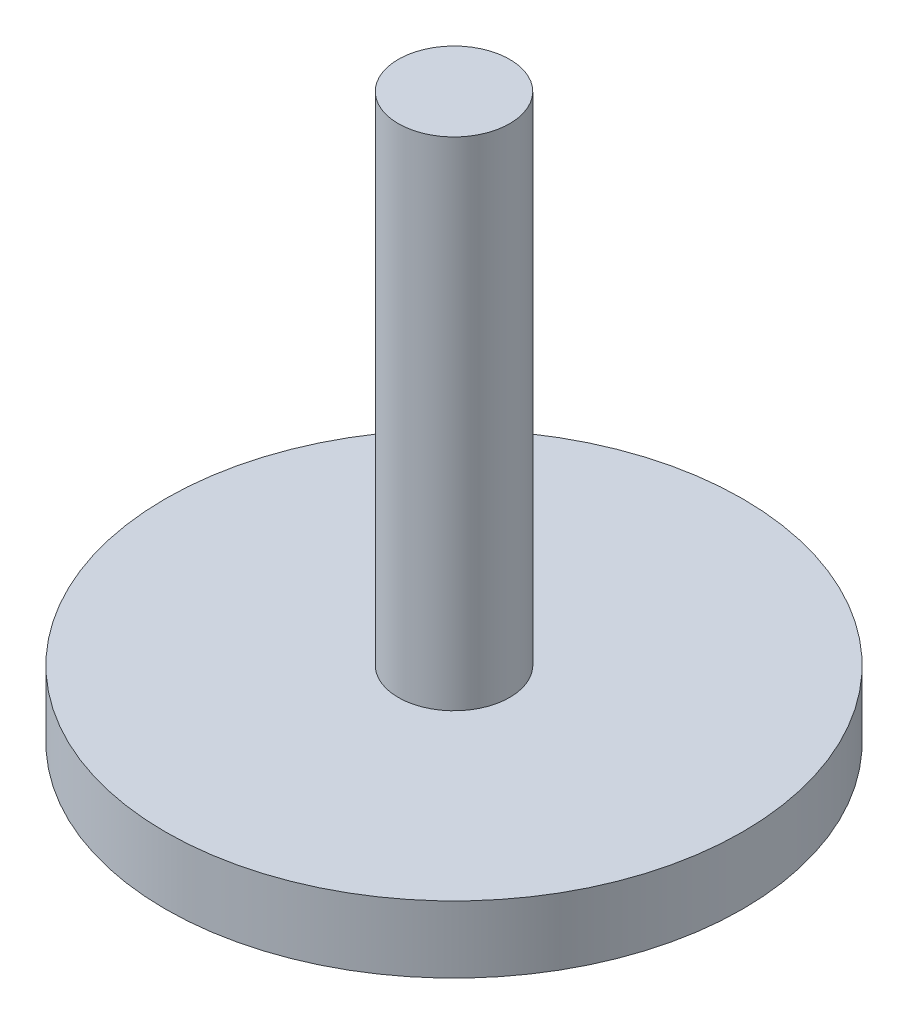
SolidWorks part; units mm, degrees
material "AISI 304"
ref_plane "Front Plane" through (0, 0, 0) normal (0, 0, 1) x (1, 0, 0)
ref_plane "Top Plane" through (0, 0, 0) normal (0, 1, 0) x (1, 0, 0)
ref_plane "Right Plane" through (0, 0, 0) normal (1, 0, 0) x (0, 0, -1)
sketch "Sketch1" plane through (0, 0, 0) normal (0, 1, 0) x (1, 0, 0)
  circle A0 centre (0, 0) radius 2.5
  dimension "D1" = 5
extrude "Boss-Extrude1" add sketch "Sketch1" along normal blind 3
sketch "Sketch2" plane through (0, 3, 0) normal (0, 1, 0) x (1, 0, 0)
  circle A0 centre (0, 0) radius 12.95
  dimension "D1" = 25.9
extrude "Boss-Extrude2" add sketch "Sketch2" along normal blind 3
sketch "Sketch3" plane through (0, 6, 0) normal (0, 1, 0) x (1, 0, 0)
  circle A0 centre (0, 0) radius 2.5
  dimension "D1" = 5
extrude "Boss-Extrude3" add sketch "Sketch3" along normal blind 22.3
equation "\"D1@Boss-Extrude3\"=28.3-3-3"
